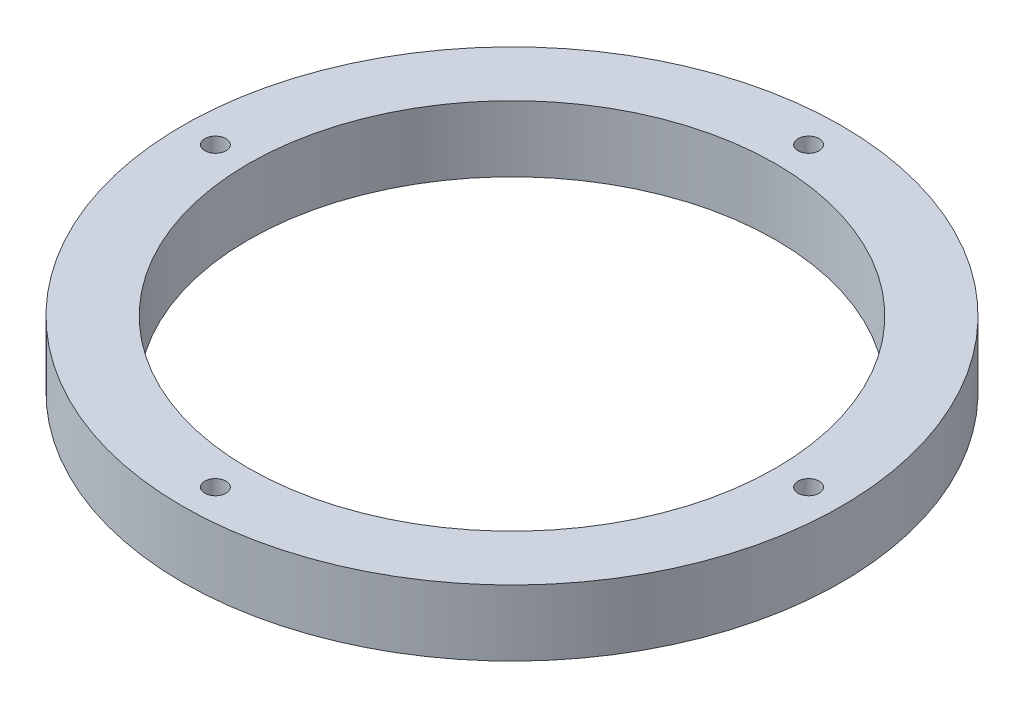
SolidWorks part; units mm, degrees
ref_plane "前视基准面" through (0, 0, 0) normal (0, 0, 1) x (1, 0, 0)
ref_plane "上视基准面" through (0, 0, 0) normal (0, 1, 0) x (1, 0, 0)
ref_plane "右视基准面" through (0, 0, 0) normal (1, 0, 0) x (0, 0, -1)
sketch "草图1" plane through (0, 0, 0) normal (0, 1, 0) x (1, 0, 0)
  circle A0 centre (0, 0) radius 40
  circle A1 centre (0, 0) radius 50
  circle A2 centre (0, 45) radius 1.6
  circle A6 centre (45, 0) radius 1.6
  circle A7 centre (0, -45) radius 1.6
  circle A8 centre (-45, 0) radius 1.6
  point P15 (0, 0)
  point P16 (0, 0)
  dimension "D1" = 80
  dimension "D2" = 10
  dimension "D3" = 3.2
  dimension "D5" = 45
  dimension "D4" = 4
extrude "凸台-拉伸1" add sketch "草图1" along normal blind 10
